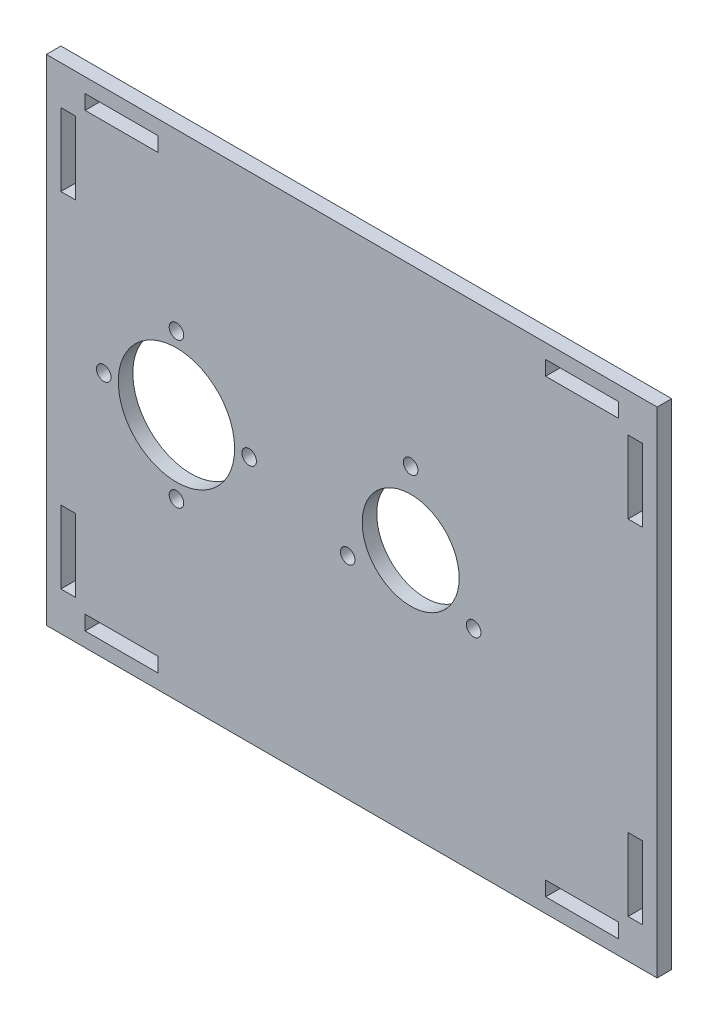
SolidWorks part; units mm, degrees
ref_plane "Front Plane" through (0, 0, 0) normal (0, 0, 1) x (1, 0, 0)
ref_plane "Top Plane" through (0, 0, 0) normal (0, 1, 0) x (1, 0, 0)
ref_plane "Right Plane" through (0, 0, 0) normal (1, 0, 0) x (0, 0, -1)
sketch "Sketch1" plane through (0, 0, 0) normal (0, 0, 1) x (1, 0, 0)
  line L0 (-48, -28) -> (-45, -28)
  line L1 (-51, 51) -> (75, 51)
  line L2 (-51, 51) -> (-51, -51)
  line L3 (-51, -51) -> (75, -51)
  line L4 (75, 51) -> (75, -51)
  line L5 (-48, 43) -> (-45, 43)
  line L6 (-48, 43) -> (-48, 28)
  line L7 (-48, 28) -> (-45, 28)
  line L8 (-45, 43) -> (-45, 28)
  line L9 (-48, 43) -> (-45, 28) construction
  line L10 (-48, 28) -> (-45, 43) construction
  line L11 (-48, -28) -> (-48, -43)
  line L12 (-48, -43) -> (-45, -43)
  line L13 (-45, -28) -> (-45, -43)
  line L14 (-48, -28) -> (-45, -43) construction
  line L15 (-48, -43) -> (-45, -28) construction
  line L16 (69, -28) -> (72, -28)
  line L17 (69, -28) -> (69, -43)
  line L18 (69, -43) -> (72, -43)
  line L19 (72, -28) -> (72, -43)
  line L20 (69, -28) -> (72, -43) construction
  line L21 (69, -43) -> (72, -28) construction
  line L22 (69, 43) -> (72, 43)
  line L23 (69, 43) -> (69, 28)
  line L24 (69, 28) -> (72, 28)
  line L25 (72, 43) -> (72, 28)
  line L26 (69, 43) -> (72, 28) construction
  line L27 (69, 28) -> (72, 43) construction
  line L29 (-43, 48) -> (-28, 48)
  line L30 (-43, 48) -> (-43, 45)
  line L31 (-43, 45) -> (-28, 45)
  line L32 (-28, 48) -> (-28, 45)
  line L33 (-43, 48) -> (-28, 45) construction
  line L34 (-43, 45) -> (-28, 48) construction
  line L35 (52, 48) -> (67, 48)
  line L36 (52, 48) -> (52, 45)
  line L37 (52, 45) -> (67, 45)
  line L38 (67, 48) -> (67, 45)
  line L39 (52, 48) -> (67, 45) construction
  line L40 (52, 45) -> (67, 48) construction
  line L41 (-43, -45) -> (-28, -45)
  line L42 (52, -45) -> (67, -45)
  line L43 (52, -45) -> (52, -48)
  line L44 (52, -48) -> (67, -48)
  line L45 (67, -45) -> (67, -48)
  line L46 (52, -45) -> (67, -48) construction
  line L47 (52, -48) -> (67, -45) construction
  line L48 (-43, -45) -> (-43, -48)
  line L49 (-43, -48) -> (-28, -48)
  line L50 (-28, -45) -> (-28, -48)
  line L51 (-43, -45) -> (-28, -48) construction
  line L52 (-43, -48) -> (-28, -45) construction
  circle A0 centre (-24.1573, 0) radius 12
  circle A1 centre (24.1573, 0) radius 10
  point P4 (-35.5, 46.5)
  point P6 (0, 0)
  point P15 (59.5, 46.5)
  point P18 (-46.5, 35.5)
  point P25 (-46.5, -35.5)
  point P30 (-35.5, -46.5)
  point P31 (59.5, -46.5)
  point P37 (70.5, -35.5)
  point P45 (70.5, 35.5)
extrude "Boss-Extrude1" add sketch "Sketch1" along normal blind 3
sketch "Sketch2" plane through (0, 0, 3) normal (0, 0, 1) x (1, 0, 0)
  circle A1 centre (24.1573, 15) radius 1.5
extrude "Cut-Extrude1" cut sketch "Sketch2" against normal blind 3
pattern_circular "CirPattern1" count 3 over 360 about axis through (24.1573, 0, 0) along (0, 0, 1) of "Cut-Extrude1"
sketch "Sketch3" plane through (0, 0, 3) normal (0, 0, 1) x (1, 0, 0)
  circle A1 centre (-24.1573, 15) radius 1.5
extrude "Cut-Extrude2" cut sketch "Sketch3" against normal blind 3
pattern_circular "CirPattern2" count 4 over 360 about axis through (-24.1573, 0, 0) along (0, 0, 1) of "Cut-Extrude2"
